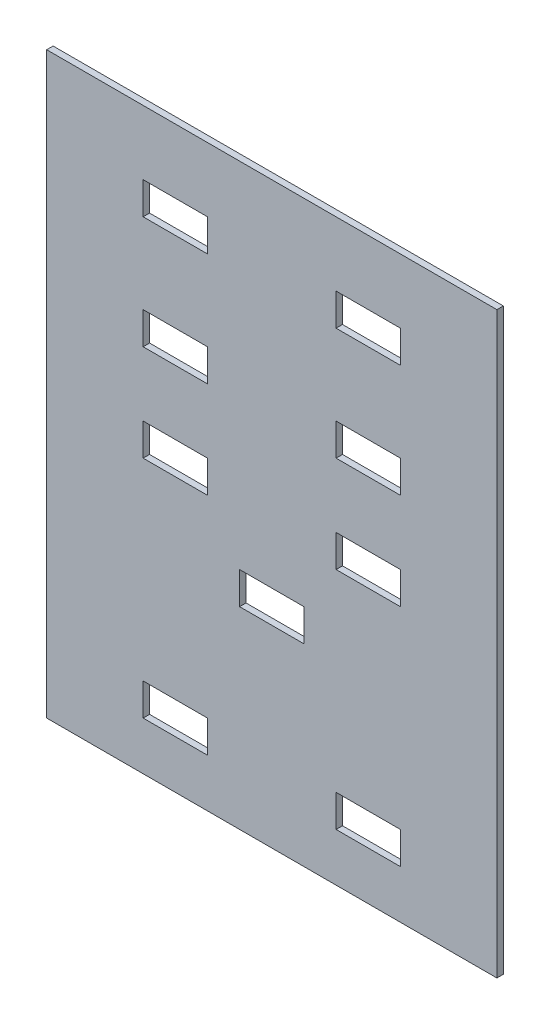
SolidWorks part; units mm, degrees
material "Brass"
ref_plane "Front Plane" through (0, 0, 0) normal (0, 0, 1) x (1, 0, 0)
ref_plane "Top Plane" through (0, 0, 0) normal (0, 1, 0) x (1, 0, 0)
ref_plane "Right Plane" through (0, 0, 0) normal (1, 0, 0) x (0, 0, -1)
sketch "Sketch1" plane through (0, 0, 0) normal (0, 0, 1) x (1, 0, 0)
  line L1 (0, 0) -> (350, 0)
  line L2 (0, 0) -> (0, 450)
  line L3 (0, 450) -> (350, 450)
  line L4 (350, 0) -> (350, 450)
  dimension "D1" = 350
  dimension "D2" = 450
extrude "Boss-Extrude1" add sketch "Sketch1" along normal blind 5
sketch "Sketch2" plane through (0, 0, 5) normal (0, 0, 1) x (1, 0, 0)
  line L2 (75, 375) -> (125, 375)
  line L3 (75, 375) -> (75, 400)
  line L4 (75, 400) -> (125, 400)
  line L5 (350, 450) -> (0, 450) construction
  line L6 (175, 450) -> (175, 207.535) construction
  line L7 (125, 375) -> (125, 400)
  line L8 (75, 375) -> (125, 400) construction
  line L9 (75, 400) -> (125, 375) construction
  point P0 (100, 387.5)
  dimension "D1" = 150
  dimension "D2" = 50
  dimension "D3" = 25
  dimension "D4" = 50
extrude "Cut-Extrude1" cut sketch "Sketch2" against normal through all
sketch "Sketch3" plane through (0, 0, 5) normal (0, 0, 1) x (1, 0, 0)
  line L0 (125, 387.5) -> (350, 387.5) construction
  line L1 (125, 375) -> (125, 400) construction
  line L2 (350, 0) -> (350, 450) construction
  line L3 (75, 375) -> (125, 375) construction
  line L4 (100, 375) -> (100, 50) construction
  line L5 (175, 62.5) -> (175, 387.5) construction
  point P7 (100, 300)
  point P10 (100, 225)
  point P11 (100, 50)
  point P16 (175, 162.5)
  point P17 (250, 387.5)
  point P18 (250, 300)
  point P19 (250, 225)
  point P20 (250, 50)
  point P21 (0, 0)
  point P22 (0, 0)
  point P23 (175, 1.469)
  point P24 (175, 0)
  point P25 (175, 91.3568)
  point P26 (237.5, 32.2258)
  point P27 (0, 0)
  point P28 (0, 0)
  point P29 (0, 0)
  point P30 (0, 0)
  point P31 (0, 0)
  point P32 (0, 0)
  point P33 (0, 0)
  point P34 (0, 0)
  point P35 (0, 0)
  point P36 (0, 0)
  point P37 (0, 0)
  point P38 (0, 0)
  point P39 (100, 375)
  dimension "D1" = 75
  dimension "D2" = 150
  dimension "D3" = 325
  dimension "D4" = 75
  dimension "D5" = 225
  dimension "D6" = 150
pattern_sketch "Sketch-Pattern2" of "Cut-Extrude1" driven by "Sketch3"
